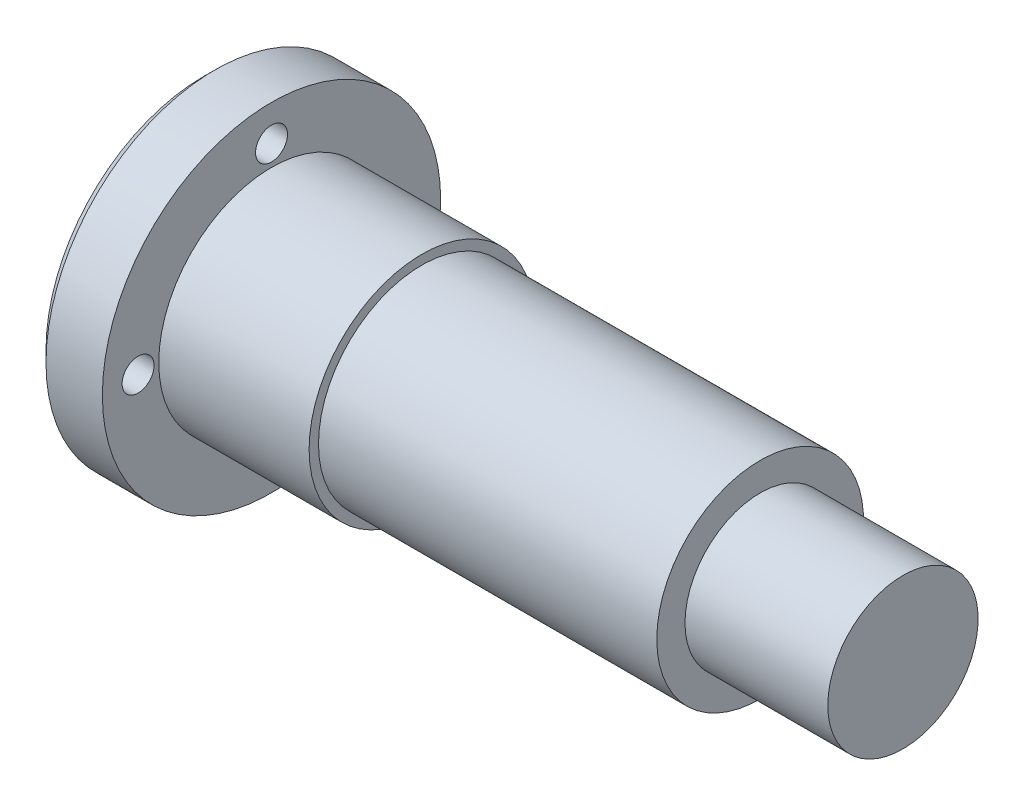
SolidWorks part; units mm, degrees
ref_plane "Front Plane" through (0, 0, 0) normal (0, 0, 1) x (1, 0, 0)
ref_plane "Top Plane" through (0, 0, 0) normal (0, 1, 0) x (1, 0, 0)
ref_plane "Right Plane" through (0, 0, 0) normal (1, 0, 0) x (0, 0, -1)
sketch "Sketch1" plane through (0, 0, 0) normal (0, 0, 1) x (1, 0, 0)
  line L0 (0, 0) -> (265.1178, 0) construction
  line L1 (189, 0) -> (189, 20)
  line L2 (189, 20) -> (151, 20)
  line L3 (151, 20) -> (151, 27.5)
  line L4 (61, 30) -> (21, 30)
  line L5 (3, 45) -> (3, 28)
  line L6 (0, 0) -> (189, 0)
  line L7 (21, 30) -> (21, 45)
  line L8 (21, 45) -> (3, 45)
  line L9 (61, 30) -> (61, 27.5)
  line L10 (61, 27.5) -> (151, 27.5)
  line L11 (0, 0) -> (0, 25)
  line L12 (0, 25) -> (3, 28)
  point P16 (6.3365, 31.3365)
  point P17 (0, -0.1692)
  dimension "D1" = 40
  dimension "D2" = 90
  dimension "D3" = 60
  dimension "D4" = 18
  dimension "D5" = 168
  dimension "D6" = 38
  dimension "D7" = 55
  dimension "D8" = 40
  dimension "D9" = 50
  dimension "D10" = 135
  dimension "D11" = 3
revolve "Revolve1" add sketch "Sketch1" angle 360 about L0
chamfer "Chamfer1" distance 3 angle 45 1 edges at (3, 0, 45)
sketch "Sketch2" plane through (3, 0, 0) normal (-1, 0, 0) x (0, 0, 1)
  circle A0 centre (0, 0) radius 35.5 construction
  circle A1 centre (35.5, 0) radius 4.25
  circle A2 centre (0, -35.5) radius 4.25
  circle A3 centre (-35.5, 0) radius 4.25
  circle A4 centre (0, 35.5) radius 4.25
  point P14 (0, 0)
  dimension "D2" = 71
  dimension "D3" = 8.5
  dimension "D1" = 4
extrude "Cut-Extrude1" cut sketch "Sketch2" against normal up to next
